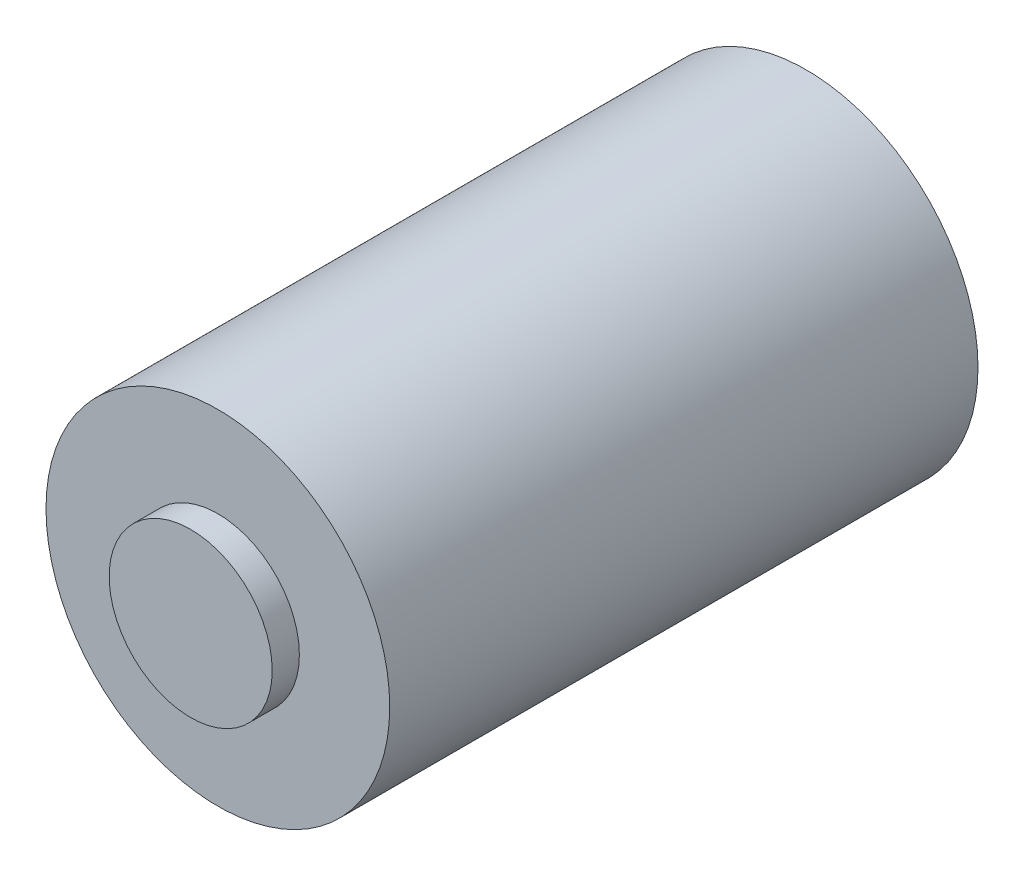
SolidWorks part; units mm, degrees
ref_plane "Front Plane" through (0, 0, 0) normal (0, 0, 1) x (1, 0, 0)
ref_plane "Top Plane" through (0, 0, 0) normal (0, 1, 0) x (1, 0, 0)
ref_plane "Right Plane" through (0, 0, 0) normal (1, 0, 0) x (0, 0, -1)
sketch "Sketch1" plane through (0, 0, 0) normal (0, 0, 1) x (1, 0, 0)
  circle A0 centre (0, 0) radius 32.131
  dimension "D1" = 64.262
extrude "Boss-Extrude1" add sketch "Sketch1" along normal blind 109.982
sketch "Sketch2" plane through (0, 0, 109.982) normal (0, 0, 1) x (1, 0, 0)
  circle A0 centre (0, 0) radius 15.24
  dimension "D1" = 30.48
extrude "Boss-Extrude2" add sketch "Sketch2" along normal blind 5.08
